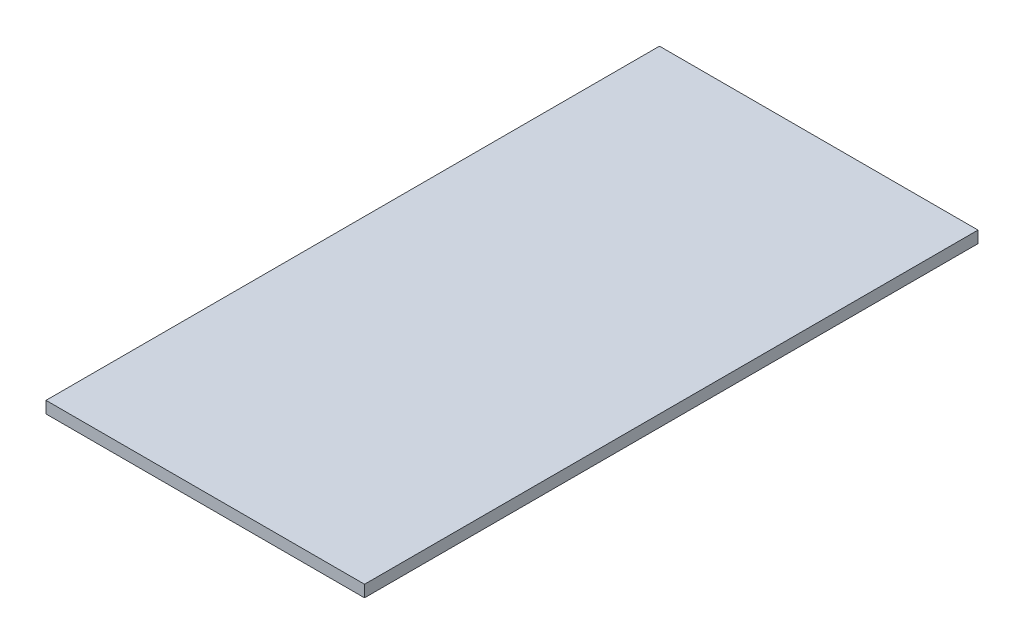
SolidWorks part; units mm, degrees
ref_plane "Front" through (0, 0, 0) normal (0, 0, 1) x (1, 0, 0)
ref_plane "Top" through (0, 0, 0) normal (0, 1, 0) x (1, 0, 0)
ref_plane "Right" through (0, 0, 0) normal (1, 0, 0) x (0, 0, -1)
sketch "Sketch1" plane through (0, 0, 0) normal (0, 1, 0) x (1, 0, 0)
  line L1 (4114.8, -7924.8) -> (-4114.8, -7924.8)
  line L2 (4114.8, -7924.8) -> (4114.8, 7924.8)
  line L3 (4114.8, 7924.8) -> (-4114.8, 7924.8)
  line L4 (-4114.8, -7924.8) -> (-4114.8, 7924.8)
  line L5 (4114.8, -7924.8) -> (-4114.8, 7924.8) construction
  line L6 (4114.8, 7924.8) -> (-4114.8, -7924.8) construction
  point P0 (0, 0)
  dimension "D1" = 15849.6
  dimension "D2" = 8229.6
extrude "Boss-Extrude1" add sketch "Sketch1" along normal blind 304.8
